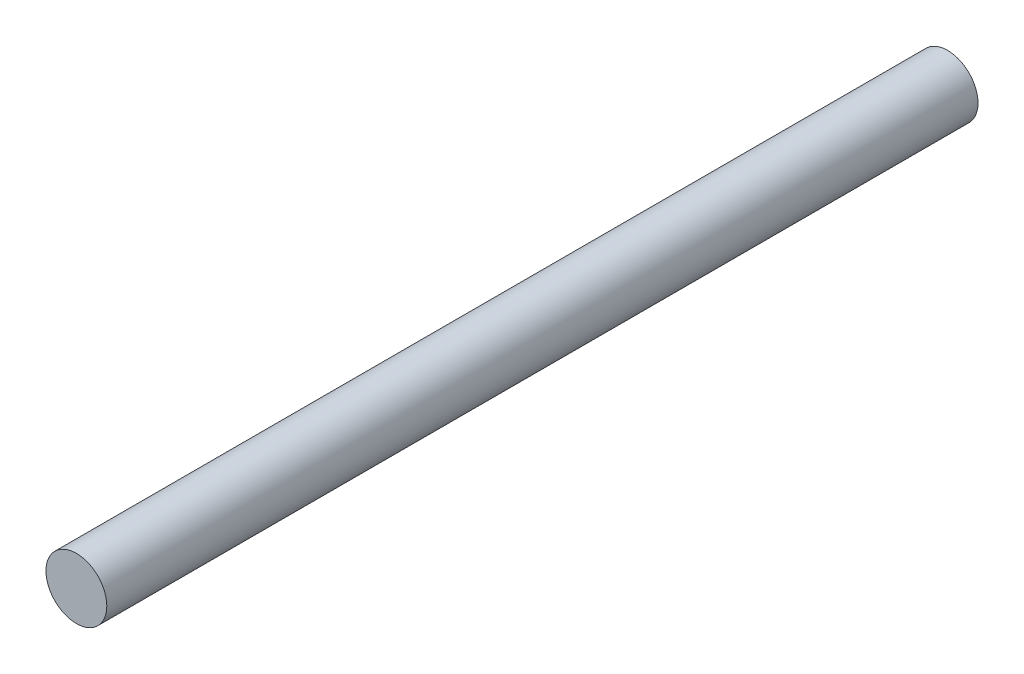
SolidWorks part; units mm, degrees
ref_plane "Front Plane" through (0, 0, 0) normal (0, 0, 1) x (1, 0, 0)
ref_plane "Top Plane" through (0, 0, 0) normal (0, 1, 0) x (1, 0, 0)
ref_plane "Right Plane" through (0, 0, 0) normal (1, 0, 0) x (0, 0, -1)
sketch "Sketch1" plane through (0, 0, 0) normal (0, 0, 1) x (1, 0, 0)
  circle A0 centre (0, 0) radius 1.7463
  dimension "D1" = 3.4925
extrude "Boss-Extrude1" add sketch "Sketch1" along normal blind 50
